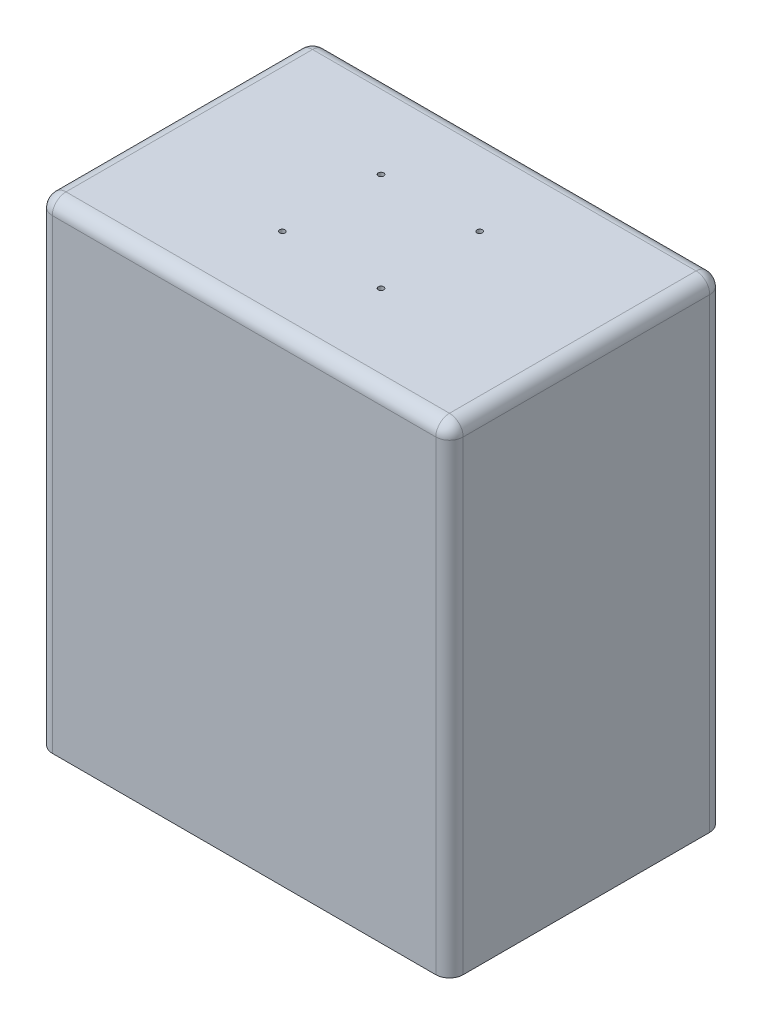
SolidWorks part; units mm, degrees
ref_plane "Plan de face" through (0, 0, 0) normal (0, 0, 1) x (1, 0, 0)
ref_plane "Plan de dessus" through (0, 0, 0) normal (0, 1, 0) x (1, 0, 0)
ref_plane "Plan de droite" through (0, 0, 0) normal (1, 0, 0) x (0, 0, -1)
sketch "Esquisse1" plane through (0, 0, 0) normal (0, 1, 0) x (1, 0, 0)
  line L0 (0, 100) -> (0, 0) construction
  line L1 (-150, 100) -> (150, 100)
  line L2 (-150, 100) -> (-150, -100)
  line L3 (-150, -100) -> (150, -100)
  line L4 (150, 100) -> (150, -100)
  line L5 (0, 0) -> (150, 0) construction
  dimension "D1" = 300
  dimension "D2" = 200
extrude "Extrusion1" add sketch "Esquisse1" along normal blind 350
shell "Coque2" thickness 5
sketch "Esquisse2" plane through (0, 350, 0) normal (0, 1, 0) x (1, 0, 0)
  line L0 (0, 0) -> (0, 100) construction
  line L1 (150, 100) -> (-150, 100) construction
  line L2 (0, 0) -> (150, 0) construction
  line L3 (150, -100) -> (150, 100) construction
  circle A0 centre (-36, 36) radius 2
  circle A1 centre (36, 36) radius 2
  circle A2 centre (-36, -36) radius 2
  circle A3 centre (36, -36) radius 2
  dimension "D1" = 4
  dimension "D2" = 36
  dimension "D3" = 36
extrude "Enlèv. mat.-Extru.1" cut sketch "Esquisse2" against normal through all
fillet "Congé1" radius 10 8 edges at (-150, 175, 100) (0, 350, 100) (150, 175, 100) (-150, 175, -100) (150, 175, -100) (-150, 350, 0) (0, 350, -100) (150, 350, 0)
